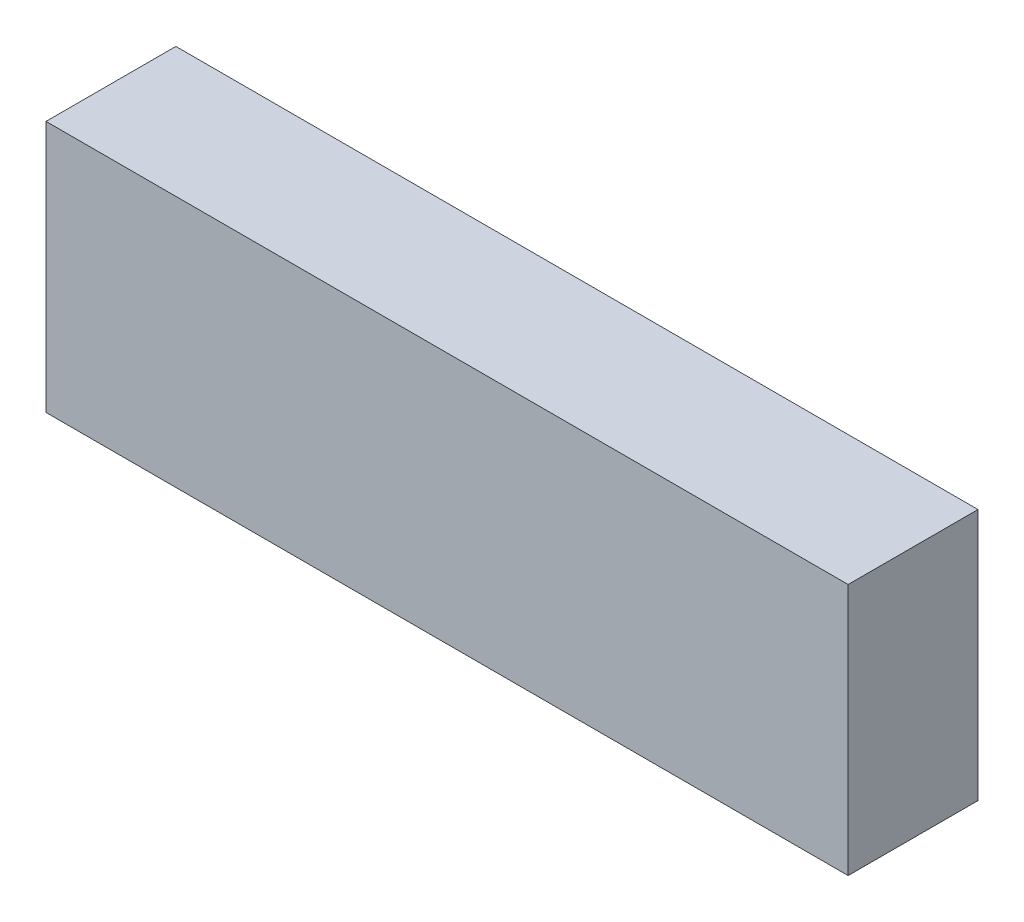
SolidWorks part; units mm, degrees
ref_plane "Front Plane" through (0, 0, 0) normal (0, 0, 1) x (1, 0, 0)
ref_plane "Top Plane" through (0, 0, 0) normal (0, 1, 0) x (1, 0, 0)
ref_plane "Right Plane" through (0, 0, 0) normal (1, 0, 0) x (0, 0, -1)
sketch "Sketch1" plane through (0, 0, 0) normal (0, 0, 1) x (1, 0, 0)
  line L1 (-52.5, -16.5) -> (52.5, -16.5)
  line L2 (-52.5, -16.5) -> (-52.5, 16.5)
  line L3 (-52.5, 16.5) -> (52.5, 16.5)
  line L4 (52.5, -16.5) -> (52.5, 16.5)
  line L5 (-52.5, -16.5) -> (52.5, 16.5) construction
  line L6 (-52.5, 16.5) -> (52.5, -16.5) construction
  point P0 (0, 0)
  dimension "D1" = 105
  dimension "D2" = 33
extrude "Boss-Extrude1" add sketch "Sketch1" along normal blind 17
